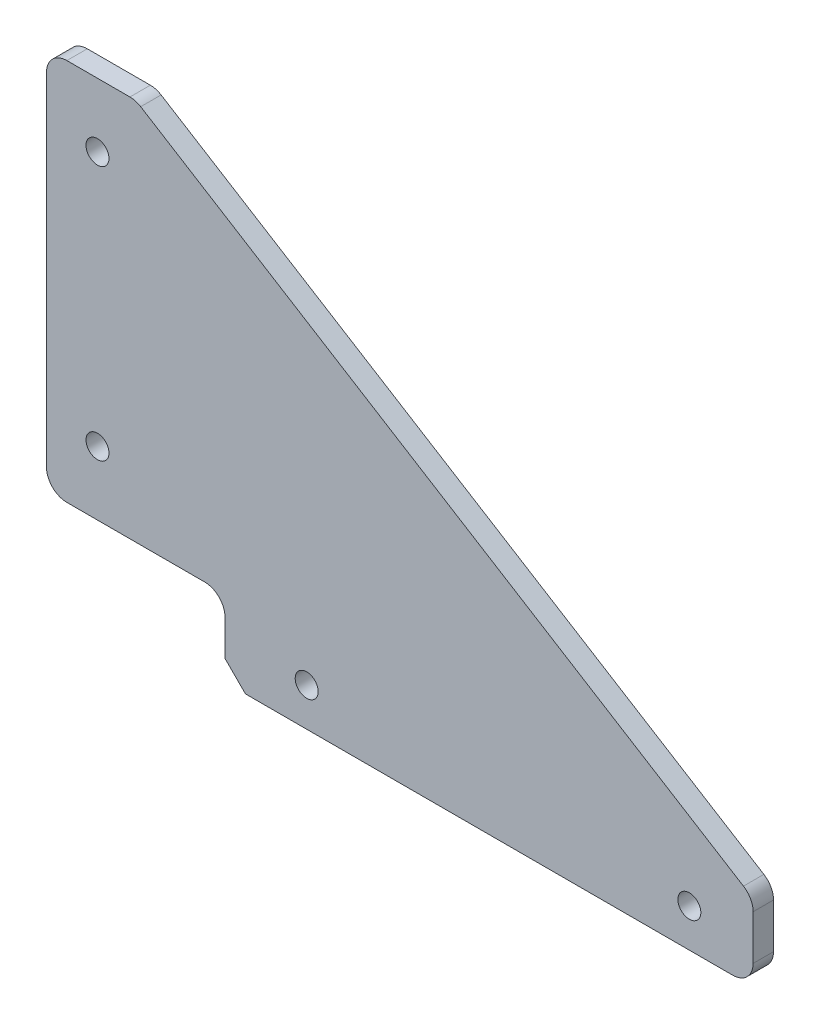
SolidWorks part; units mm, degrees
material "ASTM A36 Steel"
ref_plane "Front Plane" through (0, 0, 0) normal (0, 0, 1) x (1, 0, 0)
ref_plane "Top Plane" through (0, 0, 0) normal (0, 1, 0) x (1, 0, 0)
ref_plane "Right Plane" through (0, 0, 0) normal (1, 0, 0) x (0, 0, -1)
sketch "Sketch1" plane through (0, 0, 0) normal (0, 0, 1) x (1, 0, 0)
  line L0 (-119.3907, 123.2517) -> (-119.3907, -10.7483)
  line L1 (-111.3907, -18.7483) -> (-57.3907, -18.7483)
  line L2 (-49.3907, -26.7483) -> (-49.3907, -40.7483)
  line L3 (-41.3907, -48.7483) -> (149.6093, -48.7483)
  line L4 (157.6093, -40.7483) -> (157.6093, -23.2018)
  line L5 (153.824, -16.402) -> (-82.4542, 130.0514)
  line L6 (-86.6689, 131.2517) -> (-111.3907, 131.2517)
  line L7 (-41.3907, -48.7483) -> (-49.3907, -40.7483)
  arc A0 (-86.6689, 131.2517) -> (-82.4542, 130.0514) centre (-86.6689, 123.2517) cw
  arc A1 (153.824, -16.402) -> (157.6093, -23.2018) centre (149.6093, -23.2018) cw
  arc A2 (157.6093, -40.7483) -> (149.6093, -48.7483) centre (149.6093, -40.7483) cw
  arc A4 (-49.3907, -26.7483) -> (-57.3907, -18.7483) centre (-57.3907, -26.7483) ccw
  arc A5 (-111.3907, -18.7483) -> (-119.3907, -10.7483) centre (-111.3907, -10.7483) cw
  arc A6 (-119.3907, 123.2517) -> (-111.3907, 131.2517) centre (-111.3907, 123.2517) cw
  circle A7 centre (-99.3907, 106.2517) radius 4.5
  circle A8 centre (-99.3907, 6.2517) radius 4.5
  circle A9 centre (-17.3907, -33.7483) radius 4.5
  circle A10 centre (132.6093, -33.7483) radius 4.5
  point P9 (-84.3907, 131.2517)
  point P12 (157.6093, -18.7483)
  point P15 (157.6093, -48.7483)
  point P18 (-49.3907, -48.7483)
  point P21 (-49.3907, -18.7483)
  point P24 (-119.3907, -18.7483)
  point P27 (-119.3907, 131.2517)
  dimension "D7" = 8
  dimension "D8" = 25
  dimension "D11" = 20
  dimension "D12" = 20
  dimension "D13" = 100
  dimension "D14" = 15
  dimension "D16" = 150
  dimension "D1" = 207
  dimension "D2" = 70
  dimension "D3" = 150
  dimension "D4" = 30
  dimension "D5" = 35
  dimension "D6" = 30
  dimension "D15" = 25
extrude "Boss-Extrude1" add sketch "Sketch1" along normal blind 8
